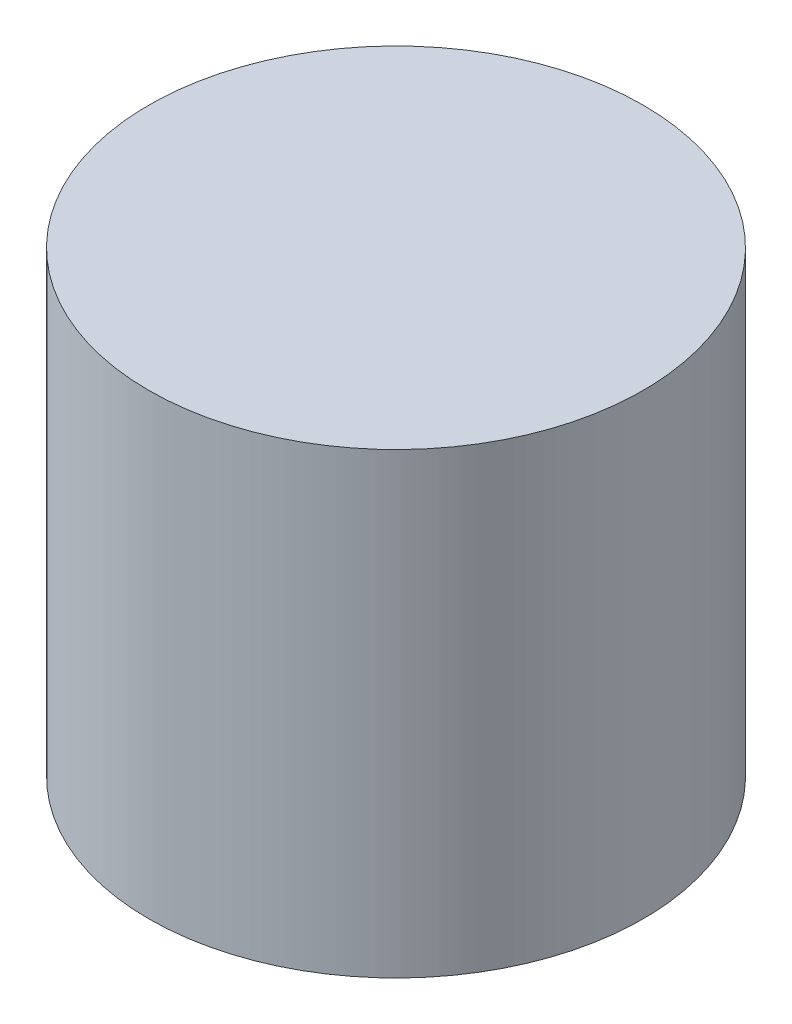
SolidWorks part; units mm, degrees
material "Polyurethane Foam Rigid"
ref_plane "Front Plane" through (0, 0, 0) normal (0, 0, 1) x (1, 0, 0)
ref_plane "Top Plane" through (0, 0, 0) normal (0, 1, 0) x (1, 0, 0)
ref_plane "Right Plane" through (0, 0, 0) normal (1, 0, 0) x (0, 0, -1)
sketch "Sketch1" plane through (0, 0, 0) normal (0, 1, 0) x (1, 0, 0)
  circle A0 centre (0, 0) radius 27.13
  dimension "D1" = 54.26
extrude "Boss-Extrude1" add sketch "Sketch1" along normal blind 50.24
